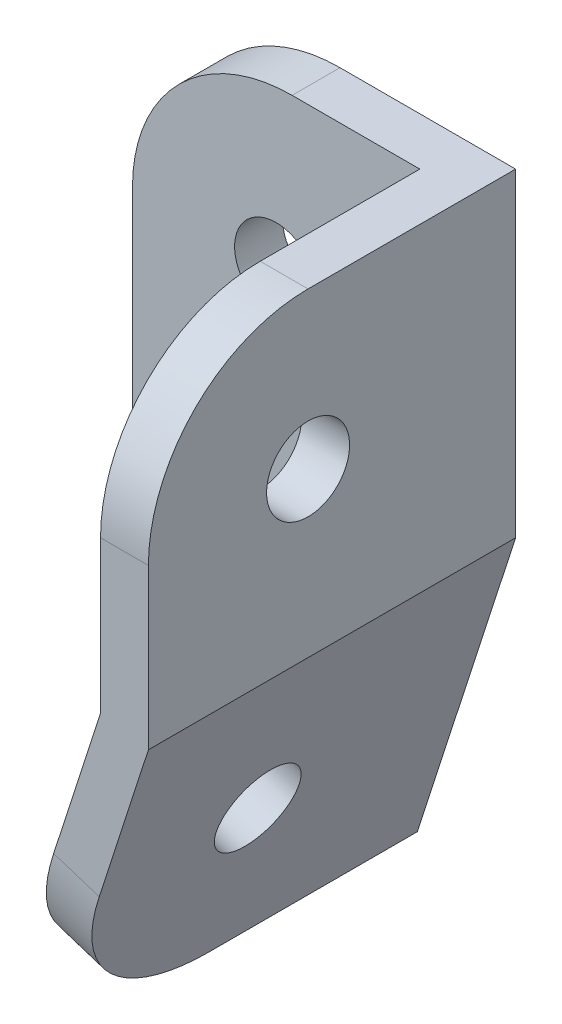
SolidWorks part; units mm, degrees
ref_plane "Plan de face" through (0, 0, 0) normal (0, 0, 1) x (1, 0, 0)
ref_plane "Plan de dessus" through (0, 0, 0) normal (0, 1, 0) x (1, 0, 0)
ref_plane "Plan de droite" through (0, 0, 0) normal (1, 0, 0) x (0, 0, -1)
sketch "Esquisse1" plane through (0, 0, 0) normal (0, 0, 1) x (1, 0, 0)
  line L0 (100, 92.65) -> (100, 112.65)
  line L1 (100, 325.5) -> (100, 92.65) construction
  line L2 (100, 112.65) -> (97, 112.65)
  line L3 (97, 112.65) -> (97, 93.1236)
  line L4 (97, 93.1236) -> (90.9848, 74.5468)
  line L5 (90.9848, 74.5468) -> (93.8389, 73.6226)
  line L6 (100, 92.65) -> (70, 0) construction
  line L7 (93.8389, 73.6226) -> (100, 92.65)
  dimension "D1" = 3
  dimension "D2" = 3
  dimension "D3" = 20
  dimension "D4" = 20
extrude "Boss.-Extru.1" add sketch "Esquisse1" along normal blind 23
sketch "Esquisse2" plane through (0, 0, 0) normal (0, 0, 1) x (1, 0, 0)
  line L0 (90.9848, 74.5468) -> (79, 74.5468)
  line L1 (79, 112.65) -> (79, 74.5468)
  line L2 (79, 112.65) -> (97, 112.65)
  line L3 (90.9848, 74.5468) -> (97, 93.1236)
  line L4 (97, 93.1236) -> (97, 112.65)
  dimension "D1" = 18
extrude "Boss.-Extru.2" add sketch "Esquisse2" along normal blind 3
sketch "Esquisse3" plane through (0, 0, 3) normal (0, 0, 1) x (1, 0, 0)
  line L0 (90.9848, 74.5468) -> (79, 78.4275)
  line L1 (79, 112.65) -> (79, 74.5468) construction
  line L2 (79, 78.4275) -> (79, 74.5468)
  line L3 (79, 74.5468) -> (90.9848, 74.5468)
  line L4 (90.9848, 74.5468) -> (93.8389, 73.6226) construction
extrude "Enlèv. mat.-Extru.1" cut sketch "Esquisse3" against normal blind 3
sketch "Esquisse4" plane through (0, 0, 3) normal (0, 0, 1) x (1, 0, 0)
  line L0 (88, 112.65) -> (88, 81.8116) construction
  line L1 (97, 112.65) -> (79, 112.65) construction
  circle A0 centre (88, 102.65) radius 2.6
  circle A1 centre (88, 82.65) radius 2.6
  dimension "D1" = 5.2
  dimension "D2" = 10
  dimension "D3" = 20
  dimension "D4" = 5.2
extrude "Enlèv. mat.-Extru.2" cut sketch "Esquisse4" against normal blind 3
sketch "Esquisse5" plane through (97, 0, 0) normal (-1, 0, 0) x (0, 0, 1)
  line L0 (3, 102.8868) -> (23, 102.8868) construction
  line L1 (3, 93.1236) -> (3, 112.65) construction
  line L2 (23, 112.65) -> (23, 93.1236) construction
  circle A0 centre (13, 102.8868) radius 2.6
  dimension "D1" = 5.2
extrude "Enlèv. mat.-Extru.3" cut sketch "Esquisse5" against normal blind 3
sketch "Esquisse6" plane through (60.5031, -19.5909, 0) normal (-0.9514, 0.3081, 0) x (0, 0, 1)
  line L0 (23, 108.7128) -> (3, 108.7128) construction
  line L1 (23, 118.476) -> (23, 98.9496) construction
  line L2 (3, 98.9496) -> (3, 118.476) construction
  circle A0 centre (13, 108.7128) radius 2.6
  dimension "D1" = 5.2
extrude "Enlèv. mat.-Extru.4" cut sketch "Esquisse6" against normal blind 3
fillet "Congé1" radius 10 4 edges at (79, 112.65, 1.5) (79, 78.4275, 1.5) (98.5, 112.65, 23) (92.4119, 74.0847, 23)
